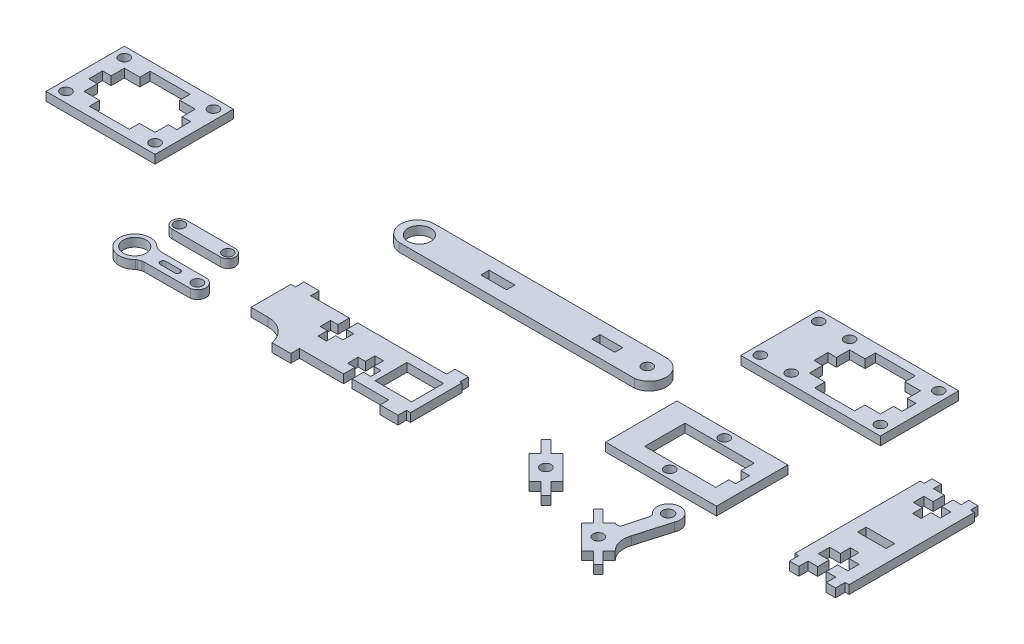
SolidWorks part; units mm, degrees
ref_plane "Front Plane" through (0, 0, 0) normal (0, 0, 1) x (1, 0, 0)
ref_plane "Top Plane" through (0, 0, 0) normal (0, 1, 0) x (1, 0, 0)
ref_plane "Right Plane" through (0, 0, 0) normal (1, 0, 0) x (0, 0, -1)
sketch "Sketch6" plane through (0, 0, -6.8736) normal (0, 1, 0) x (1, 0, 0)
  line L36 (172.3993, 17.524) -> (172.3993, 14.7799)
  line L37 (172.3993, 14.7799) -> (176.2794, 14.7799)
  line L38 (176.2794, 14.7799) -> (176.2794, 10.7799)
  line L39 (176.2794, 10.7799) -> (173.032, 10.7799)
  line L40 (173.032, 10.7799) -> (173.032, 7.063)
  line L41 (173.032, 7.063) -> (176.2794, 7.063)
  line L42 (176.2794, 7.063) -> (176.2794, 3.563)
  line L43 (176.2794, 3.563) -> (179.2794, 3.563)
  line L44 (179.2794, 3.563) -> (179.2794, 7.063)
  line L45 (179.2794, 7.063) -> (182.5439, 7.063)
  line L46 (182.5439, 7.063) -> (182.5439, 10.7799)
  line L47 (182.5439, 10.7799) -> (179.2794, 10.7799)
  line L48 (179.2794, 10.7799) -> (179.2794, 14.7799)
  line L49 (179.2794, 14.7799) -> (182.1277, 14.7799)
  line L50 (182.1277, 14.7799) -> (182.1277, 17.4216)
  line L54 (182.1277, -32.5784) -> (182.1277, -29.2201)
  line L55 (182.1277, -29.2201) -> (178.7635, -29.2201)
  line L56 (178.7635, -29.2201) -> (178.7635, -25.2201)
  line L57 (178.7635, -25.2201) -> (182.3404, -25.2201)
  line L58 (182.3404, -25.2201) -> (182.3404, -21.2526)
  line L59 (182.3404, -21.2526) -> (178.7635, -21.2526)
  line L60 (178.7635, -21.2526) -> (178.7635, -17.7526)
  line L61 (178.7635, -17.7526) -> (175.7635, -17.7526)
  line L62 (175.7635, -17.7526) -> (175.7635, -21.2526)
  line L63 (175.7635, -21.2526) -> (171.9828, -21.2526)
  line L64 (171.9828, -21.2526) -> (171.9828, -25.2201)
  line L65 (171.9828, -25.2201) -> (175.7635, -25.2201)
  line L66 (175.7635, -25.2201) -> (175.7635, -29.2201)
  line L67 (175.7635, -29.2201) -> (172.3993, -29.2201)
  line L68 (172.3993, -29.2201) -> (172.3993, -32.476)
  line L72 (172.2635, -8.7201) -> (182.2635, -8.7201)
  line L73 (182.2635, -8.7201) -> (182.2635, -11.7201)
  line L74 (182.2635, -11.7201) -> (172.2635, -11.7201)
  line L75 (172.2635, -11.7201) -> (172.2635, -8.7201)
  line L132 (186.7635, -29.2201) -> (185.3957, -29.2201)
  line L133 (185.3957, -29.2201) -> (185.3957, -32.5784)
  line L134 (167.7635, -29.2201) -> (169.1313, -29.2201)
  line L135 (169.1313, -29.2201) -> (169.1313, -32.476)
  line L136 (169.1313, 17.524) -> (169.1313, 14.7799)
  line L137 (169.1313, 14.7799) -> (167.7635, 14.7799)
  line L138 (185.3957, 17.4216) -> (185.3957, 14.7799)
  line L139 (185.3957, 14.7799) -> (186.7635, 14.7799)
  line L140 (167.7635, 14.7799) -> (167.7635, -29.2201)
  line L141 (169.1313, -32.476) -> (172.3993, -32.476)
  line L142 (182.1277, 17.4216) -> (185.3957, 17.4216)
  line L143 (186.7635, 14.7799) -> (186.7635, -29.2201)
  line L144 (185.3957, -32.5784) -> (182.1277, -32.5784)
  line L145 (169.1313, 17.524) -> (172.3993, 17.524)
  dimension "D6" = 1.3678
  dimension "D7" = 3.268
extrude "Boss-Extrude1" add sketch "Sketch6" along normal blind 3
sketch "Sketch12" plane through (0, 0, 0) normal (0, 1, 0) x (1, 0, 0)
  line L100 (4.3413, 14.5567) -> (85.6849, 14.5567)
  line L101 (3.678, 2.7449) -> (86.3482, 2.7449)
  line L103 (67.0131, 9.9945) -> (75.0131, 9.9945)
  line L104 (67.0131, 9.9945) -> (67.0131, 7.1945)
  line L105 (67.0131, 7.1945) -> (75.0131, 7.1945)
  line L106 (75.0131, 9.9945) -> (75.0131, 7.1945)
  line L107 (28.0131, 10.0945) -> (37.0131, 10.0945)
  line L108 (28.0131, 10.0945) -> (28.0131, 7.1945)
  line L109 (28.0131, 7.1945) -> (37.0131, 7.1945)
  line L110 (37.0131, 10.0945) -> (37.0131, 7.1945)
  arc A87 (4.3413, 14.5567) -> (3.678, 2.7449) centre (4.3413, 8.6322) ccw
  arc A88 (85.6849, 14.5567) -> (86.3482, 2.7449) centre (85.6849, 8.6322) cw
  circle A100 centre (5.0131, 8.5945) radius 4
  circle A101 centre (85.0131, 8.5945) radius 1.82
  dimension "D29" = 3.64
  dimension "D27" = 8
extrude "Boss-Extrude3" add sketch "Sketch12" along normal blind 3 separate body
sketch "Sketch14" plane through (0, 0, 0) normal (0, 1, 0) x (1, 0, 0)
  line L0 (20.7129, 62.7973) -> (80.7867, 62.7973)
  line L1 (80.7867, 62.7973) -> (80.7867, 17.6847)
  line L2 (80.7867, 17.6847) -> (20.7129, 17.6847)
  line L3 (20.7129, 17.6847) -> (20.7129, 62.7973)
  line L4 (28.2425, 59.822) -> (38.2425, 59.822)
  line L5 (28.2425, 59.822) -> (28.2425, 56.822)
  line L6 (28.2425, 56.822) -> (38.2425, 56.822)
  line L7 (38.2425, 59.822) -> (38.2425, 56.822)
  line L8 (63.2425, 59.822) -> (73.2425, 59.822)
  line L9 (63.2425, 59.822) -> (63.2425, 56.822)
  line L10 (63.2425, 56.822) -> (73.2425, 56.822)
  line L11 (73.2425, 59.822) -> (73.2425, 56.822)
  line L12 (74.7425, 59.822) -> (77.7425, 59.822)
  line L13 (74.7425, 59.822) -> (74.7425, 53.822)
  line L14 (74.7425, 53.822) -> (77.7425, 53.822)
  line L15 (77.7425, 59.822) -> (77.7425, 53.822)
  line L16 (74.7425, 46.822) -> (77.7425, 46.822)
  line L17 (74.7425, 46.822) -> (74.7425, 40.822)
  line L18 (74.7425, 40.822) -> (77.7425, 40.822)
  line L19 (77.7425, 46.822) -> (77.7425, 40.822)
  line L20 (29.7425, 35.822) -> (52.7425, 35.822)
  line L21 (29.7425, 35.822) -> (29.7425, 23.822)
  line L22 (29.7425, 23.822) -> (52.7425, 23.822)
  line L23 (52.7425, 35.822) -> (52.7425, 23.822)
  line L24 (23.7425, 46.822) -> (26.7425, 46.822)
  line L25 (23.7425, 46.822) -> (23.7425, 40.822)
  line L26 (23.7425, 40.822) -> (26.7425, 40.822)
  line L27 (26.7425, 46.822) -> (26.7425, 40.822)
  line L28 (23.7425, 59.822) -> (26.7425, 59.822)
  line L29 (23.7425, 59.822) -> (23.7425, 53.822)
  line L30 (23.7425, 53.822) -> (26.7425, 53.822)
  line L31 (26.7425, 59.822) -> (26.7425, 53.822)
  circle A0 centre (50.7425, 58.322) radius 1.82
  circle A1 centre (41.2425, 39.4969) radius 1.82
  circle A2 centre (41.2425, 20.3569) radius 1.82
  circle A3 centre (76.2425, 50.322) radius 1.82
  circle A4 centre (25.2425, 50.322) radius 1.82
  dimension "D1" = 19.14
  dimension "D2" = 3.64
  dimension "D3" = 3.64
  dimension "D4" = 3.64
  dimension "D5" = 3.64
extrude "Boss-Extrude4" [suppressed] add sketch "Sketch14" along normal blind 3 separate body
sketch "Sketch18" plane through (0, 0, 0) normal (0, 1, 0) x (1, 0, 0)
  line L0 (-52.2788, 74.8705) -> (7.7767, 74.8705)
  line L1 (7.7767, 74.8705) -> (7.7767, 31.3788)
  line L2 (7.7767, 31.3788) -> (0.9291, 20.5522)
  line L3 (0.9291, 20.5522) -> (-52.2788, 30.361)
  line L4 (-52.2788, 30.361) -> (-52.2788, 74.8705)
  line L5 (-44.7078, 71.6303) -> (-34.7078, 71.6303)
  line L6 (-44.7078, 71.6303) -> (-44.7078, 68.6303)
  line L7 (-44.7078, 68.6303) -> (-34.7078, 68.6303)
  line L8 (-34.7078, 71.6303) -> (-34.7078, 68.6303)
  line L9 (-49.2078, 71.6303) -> (-46.2078, 71.6303)
  line L10 (-49.2078, 71.6303) -> (-49.2078, 65.6303)
  line L11 (-49.2078, 65.6303) -> (-46.2078, 65.6303)
  line L12 (-46.2078, 71.6303) -> (-46.2078, 65.6303)
  line L13 (-49.2078, 58.6303) -> (-46.2078, 58.6303)
  line L14 (-49.2078, 58.6303) -> (-49.2078, 52.6303)
  line L15 (-49.2078, 52.6303) -> (-46.2078, 52.6303)
  line L16 (-46.2078, 58.6303) -> (-46.2078, 52.6303)
  line L17 (-43.2078, 47.6303) -> (-20.2078, 47.6303)
  line L18 (-43.2078, 47.6303) -> (-43.2078, 35.6303)
  line L19 (-43.2078, 35.6303) -> (-20.2078, 35.6303)
  line L20 (-20.2078, 47.6303) -> (-20.2078, 35.6303)
  line L21 (-9.7078, 71.6303) -> (0.2922, 71.6303)
  line L22 (-9.7078, 71.6303) -> (-9.7078, 68.6303)
  line L23 (-9.7078, 68.6303) -> (0.2922, 68.6303)
  line L24 (0.2922, 71.6303) -> (0.2922, 68.6303)
  line L25 (1.7922, 71.6303) -> (4.7922, 71.6303)
  line L26 (1.7922, 71.6303) -> (1.7922, 65.6303)
  line L27 (1.7922, 65.6303) -> (4.7922, 65.6303)
  line L28 (4.7922, 71.6303) -> (4.7922, 65.6303)
  line L29 (1.7922, 58.6303) -> (4.7922, 58.6303)
  line L30 (1.7922, 58.6303) -> (1.7922, 52.6303)
  line L31 (1.7922, 52.6303) -> (4.7922, 52.6303)
  line L32 (4.7922, 58.6303) -> (4.7922, 52.6303)
  circle A0 centre (3.3054, 62.1514) radius 1.82
  circle A1 centre (-0.9558, 24.7244) radius 1.2998
  circle A2 centre (-31.7081, 32.1289) radius 1.82
  circle A3 centre (-31.6898, 51.2689) radius 1.82
  circle A4 centre (-47.7078, 62.1303) radius 1.82
  circle A5 centre (-22.2078, 70.1303) radius 1.82
  dimension "D1" = 3.64
  dimension "D2" = 19.14
sketch "Sketch20" plane through (0, 0, 0) normal (0, 1, 0) x (1, 0, 0)
  line L0 (-3.3445, 5.1376) -> (-6.3445, 5.1376)
  line L1 (-6.3445, -0.1855) -> (-9.5309, -12.7114)
  line L2 (-21.2346, -12.8672) -> (-24.3389, -9.2481)
  line L3 (-24.3389, -9.2481) -> (-27.0786, -7.6072)
  line L4 (-27.0786, -7.6072) -> (-54.3445, -0.2275)
  line L5 (-54.3445, -0.2275) -> (-54.3445, 5.0581)
  line L6 (-54.3445, 5.0581) -> (-57.3445, 5.0581)
  line L7 (-57.3445, 5.0581) -> (-57.3445, 13.6523)
  line L8 (-57.3445, 13.6523) -> (-53.6006, 13.6523)
  line L9 (-53.6006, 13.6523) -> (-53.6006, 15.7725)
  line L10 (-53.6006, 15.7725) -> (-50.5945, 15.7725)
  line L11 (-50.5945, 15.7725) -> (-50.5945, 11.7725)
  line L12 (-50.5945, 11.7725) -> (-52.7659, 11.7725)
  line L13 (-52.7659, 11.7725) -> (-52.7659, 8.6302)
  line L14 (-52.7659, 8.6302) -> (-50.5945, 8.6302)
  line L15 (-50.5945, 8.6302) -> (-50.5945, 5.7725)
  line L16 (-50.5945, 5.7725) -> (-47.5945, 5.7725)
  line L17 (-47.5945, 5.7725) -> (-47.5945, 8.6302)
  line L18 (-47.5945, 8.6302) -> (-45.6767, 8.6302)
  line L19 (-45.6767, 8.6302) -> (-45.6767, 11.7725)
  line L20 (-45.6767, 11.7725) -> (-47.5945, 11.7725)
  line L21 (-47.5945, 11.7725) -> (-47.5945, 15.7725)
  line L22 (-47.5945, 15.7725) -> (-46.26, 15.7725)
  line L23 (-46.26, 15.7725) -> (-46.26, 14.5225)
  line L24 (-46.26, 14.5225) -> (-42.8445, 14.5225)
  line L25 (-42.8445, 14.5225) -> (-42.8445, 13.2725)
  line L26 (-42.8445, 13.2725) -> (-37.8445, 13.2725)
  line L27 (-37.8445, 13.2725) -> (-37.8445, 10.7725)
  line L28 (-37.8445, 10.7725) -> (-22.8445, 10.7725)
  line L29 (-22.8445, 10.7725) -> (-22.8445, 13.2725)
  line L30 (-22.8445, 13.2725) -> (-17.8445, 13.2725)
  line L31 (-17.8445, 13.2725) -> (-17.8445, 14.5225)
  line L32 (-17.8445, 14.5225) -> (-14.6403, 14.5225)
  line L33 (-14.6403, 14.5225) -> (-14.6403, 15.7725)
  line L34 (-14.6403, 15.7725) -> (-13.0945, 15.7725)
  line L35 (-13.0945, 15.7725) -> (-13.0945, 11.7725)
  line L36 (-13.0945, 11.7725) -> (-15.4488, 11.7725)
  line L37 (-15.4488, 11.7725) -> (-15.4488, 8.6851)
  line L38 (-15.4488, 8.6851) -> (-13.0945, 8.6851)
  line L39 (-13.0945, 8.6851) -> (-13.0945, 5.7725)
  line L40 (-13.0945, 5.7725) -> (-10.0945, 5.7725)
  line L41 (-10.0945, 5.7725) -> (-10.0945, 8.6674)
  line L42 (-10.0945, 8.6674) -> (-7.5507, 8.6674)
  line L43 (-7.5507, 8.6674) -> (-7.5507, 11.7725)
  line L44 (-7.5507, 11.7725) -> (-10.0945, 11.7725)
  line L45 (-10.0945, 11.7725) -> (-10.0945, 15.7725)
  line L46 (-10.0945, 15.7725) -> (-7.0098, 15.7725)
  line L47 (-7.0098, 15.7725) -> (-7.0098, 13.684)
  line L48 (-7.0098, 13.684) -> (-3.3445, 13.6514)
  line L49 (-3.3445, 13.6514) -> (-3.3445, 5.1376)
  line L50 (-6.3445, 5.1376) -> (-6.3445, -0.1855)
  arc A0 (-9.5309, -12.7114) -> (-21.2346, -12.8672) centre (-15.4037, -11.2174) cw
  circle A1 centre (-15.3445, -11.2275) radius 1.82
  dimension "D1" = 3.64
sketch "Sketch22" plane through (0, 0, 0) normal (0, 1, 0) x (1, 0, 0)
  line L0 (-22.8304, -83.5062) -> (5.98, -82.8529)
  line L1 (18.5125, -82.749) -> (92.2578, -82.749)
  line L2 (92.3104, -90.7487) -> (18.5715, -91.7184)
  line L3 (6.0387, -91.7793) -> (-22.7778, -91.5049)
  arc A0 (5.98, -82.8529) -> (10.0623, -81.6918) centre (5.7889, -74.4239) ccw
  arc A1 (10.0623, -81.6918) -> (10.658, -81.4927) centre (10.8295, -82.9967) cw
  arc A2 (10.658, -81.4927) -> (11.2714, -81.3569) centre (10.3161, -78.495) ccw
  arc A3 (11.2714, -81.3569) -> (11.8955, -81.2861) centre (11.7502, -82.7912) cw
  arc A4 (11.8955, -81.2861) -> (12.5237, -81.2808) centre (12.1844, -78.2942) ccw
  arc A5 (12.5237, -81.2808) -> (13.1489, -81.3413) centre (12.6941, -82.7806) cw
  arc A6 (13.1489, -81.3413) -> (13.7644, -81.4668) centre (14.0525, -78.4818) ccw
  arc A7 (13.7644, -81.4668) -> (14.3634, -81.656) centre (13.6195, -82.9685) cw
  arc A8 (14.3634, -81.656) -> (14.9394, -81.9067) centre (15.8391, -79.0526) ccw
  arc A9 (14.9394, -81.9067) -> (15.6165, -82.2065) centre (13.9387, -85.0813) cw
  arc A10 (15.6165, -82.2065) -> (16.3185, -82.4423) centre (16.5367, -80.6298) ccw
  arc A11 (16.3185, -82.4423) -> (17.0393, -82.6122) centre (15.9213, -85.7415) cw
  arc A12 (17.0393, -82.6122) -> (17.7727, -82.7147) centre (17.6534, -80.8935) ccw
  arc A13 (17.7727, -82.7147) -> (18.5125, -82.749) centre (17.9898, -86.0281) cw
  arc A14 (92.2578, -82.749) -> (92.3104, -90.7487) centre (92.2578, -86.7491) cw
  arc A15 (18.5715, -91.7184) -> (14.4371, -92.8659) centre (18.6822, -100.1392) ccw
  arc A16 (14.4371, -92.8659) -> (13.8407, -93.0629) centre (13.6751, -91.5605) cw
  arc A17 (13.8407, -93.0629) -> (13.2269, -93.1965) centre (14.1702, -96.0538) ccw
  arc A18 (13.2269, -93.1965) -> (12.6025, -93.2652) centre (12.753, -91.7611) cw
  arc A19 (12.6025, -93.2652) -> (11.9743, -93.2682) centre (12.3027, -96.2616) ccw
  arc A20 (11.9743, -93.2682) -> (11.3493, -93.2055) centre (11.8094, -91.7654) cw
  arc A21 (11.3493, -93.2055) -> (10.7342, -93.0779) centre (10.4346, -96.0685) ccw
  arc A22 (10.7342, -93.0779) -> (10.1359, -92.8866) centre (10.8846, -91.5762) cw
  arc A23 (10.1359, -92.8866) -> (9.5608, -92.6338) centre (8.6482, -95.4904) ccw
  arc A24 (9.5608, -92.6338) -> (8.8936, -92.3352) centre (10.5595, -89.5075) cw
  arc A25 (8.8936, -92.3352) -> (8.202, -92.0988) centre (7.9736, -93.8967) ccw
  arc A26 (8.202, -92.0988) -> (7.4916, -91.9264) centre (8.615, -88.8472) cw
  arc A27 (7.4916, -91.9264) -> (6.7685, -91.8196) centre (6.8709, -93.6279) ccw
  arc A28 (6.7685, -91.8196) -> (6.0387, -91.7793) centre (6.5832, -88.5467) cw
  arc A29 (-22.7778, -91.5049) -> (-22.8304, -83.5062) centre (-22.7397, -87.5052) cw
  circle A30 centre (-22.7398, -87.5051) radius 1.925
  circle A31 centre (12.2595, -87.275) radius 1.925
  circle A32 centre (92.2578, -86.749) radius 1.925
  dimension "D1" = 3.85
  dimension "D2" = 3.85
sketch "Sketch23" plane through (0, 0, 0) normal (0, 1, 0) x (1, 0, 0)
  line L0 (62.0938, -102.6123) -> (-12.185, -101.1529)
  line L1 (62.0145, -110.6115) -> (-11.7091, -110.5993)
  arc A0 (-18.7722, -99.8781) -> (-23.9525, -106.2408) centre (-18.181, -105.6496) ccw
  arc A1 (-23.9525, -106.2408) -> (-20.8301, -111.1061) centre (-17.5842, -105.5884) ccw
  arc A2 (-20.8301, -111.1061) -> (-15.5368, -111.3053) centre (-17.9986, -106.2928) ccw
  arc A3 (-15.5368, -111.3053) -> (-13.6142, -110.7239) centre (-12.8064, -116.8649) cw
  arc A4 (-13.6142, -110.7239) -> (-11.7091, -110.5993) centre (-11.7115, -125.1879) cw
  arc A5 (-18.7722, -99.8781) -> (-14.8108, -100.6548) centre (-18.0664, -106.7687) cw
  arc A6 (-14.8108, -100.6548) -> (-13.5188, -101.0143) centre (-13.353, -97.9172) ccw
  arc A7 (-13.5188, -101.0143) -> (-12.185, -101.1529) centre (-14.2348, -114.3916) cw
  arc A8 (62.0938, -102.6123) -> (62.0145, -110.6115) centre (62.0152, -106.6115) cw
  circle A9 centre (62.0152, -106.6115) radius 1.925
  circle A10 centre (-17.9809, -105.8257) radius 1.925
  dimension "D1" = 3.85
  dimension "D2" = 3.85
sketch "Sketch24" plane through (0, 0, 0) normal (0, 1, 0) x (1, 0, 0)
  line L0 (-90.2893, -24.7085) -> (-67.8284, -24.7085)
  line L1 (-90.2954, -32.7085) -> (-67.194, -32.744)
  line L2 (-75.2787, -28.7329) -> (-70.3703, -28.7329) construction
  line L3 (-75.2787, -27.7198) -> (-70.3703, -27.7198)
  line L4 (-75.2787, -29.7461) -> (-70.3703, -29.7461)
  arc A0 (-67.8284, -24.7085) -> (-62.5705, -23.1591) centre (-67.8284, -15.0125) ccw
  arc A1 (-62.5705, -23.1591) -> (-54.9836, -31.523) centre (-60.3229, -28.7434) cw
  arc A2 (-54.9836, -31.523) -> (-63.9473, -33.5823) centre (-60.343, -28.7329) cw
  arc A3 (-67.194, -32.744) -> (-63.9473, -33.5823) centre (-67.2043, -39.4905) cw
  arc A4 (-75.2787, -27.7198) -> (-75.2787, -29.7461) centre (-75.2787, -28.7329) ccw
  arc A5 (-70.3703, -29.7461) -> (-70.3703, -27.7198) centre (-70.3703, -28.7329) ccw
  circle A6 centre (-90.2893, -28.7085) radius 1.925
  circle A7 centre (-60.2893, -28.7085) radius 4
  arc A8 (-90.2954, -32.7085) -> (-90.2893, -24.7085) centre (-90.2893, -28.7085) cw
  point P13 (-72.8245, -28.7329)
  dimension "D1" = 3.85
  dimension "D2" = 8
sketch "Sketch26" plane through (0, 0, 0) normal (0, 1, 0) x (1, 0, 0)
  line L0 (-87.7528, 74.718) -> (-87.4104, 72.6313)
  line L1 (-87.7528, 74.718) -> (-88.0164, 76.816)
  arc A0 (-88.0164, 76.816) -> (-95.8236, 75.1147) centre (-92.0067, 76.3629) ccw
  arc A1 (-95.8236, 75.1147) -> (-95.7872, 31.4073) centre (-162.8228, 53.2052) cw
  arc A2 (-95.7872, 31.4073) -> (-88.3346, 28.5226) centre (-91.9816, 30.1698) ccw
  arc A3 (-88.3346, 28.5226) -> (-75.123, 36.3095) centre (-76.205, 23.044) cw
  arc A4 (-75.123, 36.3095) -> (-71.9331, 43.1193) centre (-74.7969, 40.3087) ccw
  arc A5 (-71.9331, 43.1193) -> (-87.4104, 72.6313) centre (-30.7636, 83.5248) cw
  circle A6 centre (-74.764, 40.2933) radius 1.82
  circle A7 centre (-91.9939, 30.1381) radius 1.82
  circle A8 centre (-91.9939, 76.3923) radius 1.82
  dimension "D1" = 3.64
  dimension "D2" = 3.64
  dimension "D3" = 3.64
sketch "Sketch27" plane through (0, 0, 0) normal (0, 1, 0) x (1, 0, 0)
  line L0 (-91.9831, 11.0737) -> (-77.9831, 11.0737)
  line L1 (-104.1231, 14.1616) -> (-65.8431, 14.1616)
  line L2 (-104.1231, 14.1616) -> (-104.1231, -13.3284)
  line L3 (-104.1231, -13.3284) -> (-65.8431, -13.3284)
  line L4 (-65.8431, 14.1616) -> (-65.8431, -13.3284)
  line L5 (-77.9831, 11.0737) -> (-77.9831, 7.4737)
  line L6 (-77.9831, 7.4737) -> (-72.5331, 7.4737)
  line L7 (-72.5331, 7.4737) -> (-72.5331, 2.8437)
  line L8 (-69.5331, 2.8437) -> (-69.5331, -2.0063)
  line L9 (-69.5331, -2.0063) -> (-72.5331, -2.0063)
  line L10 (-72.5331, -2.0063) -> (-72.5331, -6.6363)
  line L11 (-72.5331, -6.6363) -> (-77.9831, -6.6363)
  line L12 (-77.9831, -6.6363) -> (-77.9831, -10.2363)
  line L13 (-77.9831, -10.2363) -> (-91.9831, -10.2363)
  line L14 (-91.9831, -10.2363) -> (-91.9831, -6.6384)
  line L15 (-91.9831, -6.6384) -> (-97.4331, -6.6384)
  line L16 (-97.4331, -6.6384) -> (-97.4331, -2.0084)
  line L17 (-97.4331, -2.0084) -> (-100.4331, -2.0084)
  line L18 (-100.4331, -2.0084) -> (-100.4331, 2.8416)
  line L19 (-100.4331, 2.8416) -> (-97.4331, 2.8416)
  line L20 (-97.4331, 2.8416) -> (-97.4331, 7.4716)
  line L21 (-97.4331, 7.4716) -> (-91.9831, 7.4716)
  line L22 (-91.9831, 7.4716) -> (-91.9831, 11.0737)
  line L23 (-72.5331, 2.8437) -> (-69.5331, 2.8437)
  circle A0 centre (-100.6231, 10.6616) radius 1.82
  circle A1 centre (-100.6231, -9.8284) radius 1.82
  circle A2 centre (-69.3431, -9.8263) radius 1.82
  circle A3 centre (-69.3431, 10.6616) radius 1.82
  dimension "D1" = 3.64
  dimension "D2" = 14
  dimension "D3" = 3.6
  dimension "D4" = 3.6
  dimension "D5" = 4.85
  dimension "D6" = 4.63
  dimension "D7" = 3.19
  dimension "D8" = 3.19
  dimension "D9" = 3.19
  dimension "D10" = 5.45
  dimension "D11" = 3
  dimension "D12" = 3.19
  dimension "D13" = 3.19
  dimension "D14" = 3.19
  dimension "D15" = 3.5
  dimension "D16" = 3.5
  dimension "D17" = 3.5
sketch "Sketch28" plane through (0, 0, 0) normal (0, 1, 0) x (1, 0, 0)
  line L0 (108.8597, -2.0432) -> (133.1497, -2.0432)
  line L1 (100.7124, 3.3321) -> (139.6281, 3.3321)
  line L2 (100.7124, 3.3321) -> (100.7124, -21.7433)
  line L3 (100.7124, -21.7433) -> (139.6281, -21.7433)
  line L4 (139.6281, 3.3321) -> (139.6281, -21.7433)
  line L5 (133.1497, -2.0432) -> (133.1497, -6.6732)
  line L6 (133.1497, -6.6732) -> (136.1497, -6.6732)
  line L7 (136.1497, -6.6732) -> (136.1497, -11.5232)
  line L8 (136.1497, -11.5232) -> (133.7949, -11.5232)
  line L9 (133.7949, -11.5232) -> (133.7949, -16.1532)
  line L10 (133.7949, -16.1532) -> (108.8597, -16.1532)
  line L11 (108.8597, -16.1532) -> (108.8597, -2.0432)
  circle A0 centre (120.2396, 0.384) radius 1.82
  circle A1 centre (120.2396, -18.756) radius 1.82
  dimension "D1" = 3.64
  dimension "D2" = 3.64
  dimension "D3" = 3
  dimension "D4" = 24.29
  dimension "D5" = 4.85
  dimension "D6" = 4.63
  dimension "D7" = 19.14
sketch "Sketch29" plane through (0, 0, 0) normal (0, 1, 0) x (1, 0, 0)
  line L0 (120.9256, 52.7526) -> (134.9256, 52.7526)
  line L1 (98.079, 55.8405) -> (147.0656, 55.8405)
  line L2 (98.079, 55.8405) -> (98.079, 28.3505)
  line L3 (98.079, 28.3505) -> (147.0656, 28.3505)
  line L4 (147.0656, 55.8405) -> (147.0656, 28.3505)
  line L5 (134.9256, 52.7526) -> (134.9256, 49.1526)
  line L6 (134.9256, 49.1526) -> (140.3756, 49.1526)
  line L7 (140.3756, 49.1526) -> (140.3756, 44.5226)
  line L8 (143.3756, 44.5226) -> (143.3756, 39.6726)
  line L9 (143.3756, 39.6726) -> (140.3756, 39.6726)
  line L10 (140.3756, 39.6726) -> (140.3756, 35.0426)
  line L11 (140.3756, 35.0426) -> (134.9256, 35.0426)
  line L12 (134.9256, 35.0426) -> (134.9256, 31.4426)
  line L13 (134.9256, 31.4426) -> (120.9256, 31.4426)
  line L14 (120.9256, 31.4426) -> (120.9256, 35.0405)
  line L15 (120.9256, 35.0405) -> (115.4756, 35.0405)
  line L16 (115.4756, 35.0405) -> (115.4756, 39.6705)
  line L17 (115.4756, 39.6705) -> (112.4756, 39.6705)
  line L18 (112.4756, 39.6705) -> (112.4756, 44.5205)
  line L19 (112.4756, 44.5205) -> (115.4756, 44.5205)
  line L20 (115.4756, 44.5205) -> (115.4756, 49.1505)
  line L21 (115.4756, 49.1505) -> (120.9256, 49.1505)
  line L22 (120.9256, 49.1505) -> (120.9256, 52.7526)
  line L23 (140.3756, 44.5226) -> (143.3756, 44.5226)
  circle A0 centre (112.2856, 52.3405) radius 1.82
  circle A1 centre (112.2856, 31.8505) radius 1.82
  circle A2 centre (143.5656, 31.8526) radius 1.82
  circle A3 centre (143.5656, 52.3405) radius 1.82
  circle A4 centre (101.4197, 52.3405) radius 1.82
  circle A5 centre (101.4197, 31.8505) radius 1.82
  dimension "D1" = 3.64
  dimension "D2" = 14
  dimension "D3" = 3.6
  dimension "D4" = 3.6
  dimension "D5" = 4.85
  dimension "D6" = 4.63
  dimension "D7" = 3.19
  dimension "D8" = 3.19
  dimension "D9" = 3.19
  dimension "D10" = 5.45
  dimension "D11" = 3
  dimension "D12" = 3.19
  dimension "D13" = 3.1879
  dimension "D14" = 3.19
  dimension "D15" = 3.5
  dimension "D16" = 3.5
  dimension "D17" = 20.49
sketch "Sketch30" plane through (0, 0, 0) normal (0, 1, 0) x (1, 0, 0)
  line L0 (17.989, -28.9872) -> (4.4448, -28.9872)
  line L1 (11.9231, -50.0571) -> (18.5165, -50.0571)
  line L2 (18.5165, -50.0571) -> (18.5165, -46.9872)
  line L3 (18.5165, -46.9872) -> (33.989, -46.9872)
  line L4 (33.989, -46.9872) -> (33.989, -42.9872)
  line L5 (33.989, -42.9872) -> (31.4392, -42.9872)
  line L6 (31.4392, -42.9872) -> (31.4392, -39.3422)
  line L7 (31.4392, -39.3422) -> (33.989, -39.3422)
  line L8 (33.989, -39.3422) -> (33.989, -35.9872)
  line L9 (33.989, -35.9872) -> (36.989, -35.9872)
  line L10 (36.989, -35.9872) -> (36.989, -39.3774)
  line L11 (36.989, -39.3774) -> (39.5388, -39.3774)
  line L12 (39.5388, -39.3774) -> (39.5388, -42.9872)
  line L13 (39.5388, -42.9872) -> (36.989, -42.9872)
  line L14 (36.989, -42.9872) -> (36.989, -46.9872)
  line L15 (36.989, -46.9872) -> (49.8067, -46.9872)
  line L16 (49.8067, -46.9872) -> (49.8067, -49.9872)
  line L17 (52.1127, -25.9872) -> (52.1127, -28.9872)
  line L18 (52.1127, -28.9872) -> (20.989, -28.9872)
  line L19 (20.989, -28.9872) -> (20.989, -32.9872)
  line L20 (20.989, -32.9872) -> (23.539, -32.9872)
  line L21 (23.539, -32.9872) -> (23.539, -36.7505)
  line L22 (23.539, -36.7505) -> (20.989, -36.7505)
  line L23 (20.989, -36.7505) -> (20.989, -39.9872)
  line L24 (20.989, -39.9872) -> (17.989, -39.9872)
  line L25 (17.989, -39.9872) -> (17.989, -36.6921)
  line L26 (17.989, -36.6921) -> (15.439, -36.6921)
  line L27 (15.439, -36.6921) -> (15.439, -32.9872)
  line L28 (15.439, -32.9872) -> (17.989, -32.9872)
  line L29 (17.989, -32.9872) -> (17.989, -28.9872)
  line L30 (4.4448, -28.9872) -> (4.4448, -25.9872)
  line L31 (41.6011, -32.3441) -> (54.4301, -32.3441)
  line L32 (41.6011, -32.3441) -> (41.6011, -43.5339)
  line L33 (41.6011, -43.5339) -> (54.4301, -43.5339)
  line L34 (54.4301, -32.3441) -> (54.4301, -43.5339)
  line L35 (-2.511, -42.9872) -> (3.489, -42.9872)
  line L36 (-0.8977, -25.9872) -> (-0.8977, -28.9872)
  line L37 (-0.8977, -28.9872) -> (-2.511, -28.9872)
  line L38 (56.0898, -49.9872) -> (56.0898, -46.9872)
  line L39 (56.0898, -46.9872) -> (57.489, -46.9872)
  line L40 (56.7962, -25.9872) -> (56.7962, -28.9872)
  line L41 (56.7962, -28.9872) -> (57.489, -28.9872)
  line L42 (57.489, -28.9872) -> (57.489, -46.9872)
  line L43 (56.0898, -49.9872) -> (49.8067, -49.9872)
  line L44 (56.7962, -25.9872) -> (52.1127, -25.9872)
  line L45 (-0.8977, -25.9872) -> (4.4448, -25.9872)
  line L46 (-2.511, -42.9872) -> (-2.511, -28.9872)
  arc A0 (3.489, -42.9872) -> (11.9231, -50.0571) centre (3.489, -51.5529) cw
  dimension "D1" = 3.645
  dimension "D2" = 2.5498
  dimension "D3" = 2.55
  dimension "D4" = 2.55
  dimension "D5" = 2.55
  dimension "D6" = 2.55
sketch "Sketch31" plane through (0, 0, 0) normal (0, 1, 0) x (1, 0, 0)
  line L0 (-40.1799, -27.8411) -> (-23.1799, -27.8411)
  line L1 (-23.1799, -33.0411) -> (-40.1799, -33.0411)
  arc A0 (-23.1799, -27.8411) -> (-23.1799, -33.0411) centre (-23.1799, -30.4411) cw
  arc A1 (-40.1799, -33.0411) -> (-40.1799, -27.8411) centre (-40.1799, -30.4411) cw
  circle A2 centre (-40.1799, -30.4411) radius 1.82
  circle A3 centre (-23.1799, -30.4411) radius 1.82
  dimension "D1" = 3.64
  dimension "D2" = 3.64
  dimension "D3" = 2.6
  dimension "D4" = 2.6
  dimension "D5" = 2.6
sketch "Sketch32" plane through (0, 0, 0) normal (0, 1, 0) x (1, 0, 0)
  line L0 (-19.3691, -41.9276) -> (-34.5684, -41.9276)
  line L1 (-18.8998, -47.8907) -> (-35.1542, -47.962)
  line L2 (-35.1542, -47.962) -> (-35.7319, -48.0649)
  line L3 (-31.4441, -44.9276) -> (-26.3849, -44.9276) construction
  line L4 (-31.4441, -43.9544) -> (-26.3849, -43.9544)
  line L5 (-31.4441, -45.9008) -> (-26.3849, -45.9008)
  arc A0 (-34.5684, -41.9276) -> (-38.333, -40.3416) centre (-34.5684, -36.6667) cw
  arc A1 (-38.333, -40.3416) -> (-42.1025, -50.3785) centre (-41.3099, -44.9499) ccw
  arc A2 (-42.1025, -50.3785) -> (-37.3382, -48.7649) centre (-41.3026, -44.9) ccw
  arc A3 (-37.3382, -48.7649) -> (-36.8315, -48.4691) centre (-36.5499, -49.5334) cw
  arc A4 (-36.8315, -48.4691) -> (-35.7319, -48.0649) centre (-38.4338, -42.4122) ccw
  arc A5 (-19.3691, -41.9276) -> (-18.8998, -47.8907) centre (-19.3691, -44.9276) cw
  arc A6 (-31.4441, -43.9544) -> (-31.4441, -45.9008) centre (-31.4441, -44.9276) ccw
  arc A7 (-26.3849, -45.9008) -> (-26.3849, -43.9544) centre (-26.3849, -44.9276) ccw
  circle A8 centre (-41.3691, -44.9276) radius 4
  circle A9 centre (-19.3691, -44.9276) radius 1.82
  point P17 (-28.9145, -44.9276)
  dimension "D1" = 3.64
sketch "Sketch33" plane through (0, 0, 0) normal (0, 1, 0) x (1, 0, 0)
  line L0 (-4.2145, -66.2122) -> (75.574, -66.2122) construction
  line L1 (-4.2145, -62.1261) -> (75.574, -62.1261)
  line L2 (-4.2145, -70.2983) -> (75.574, -70.2983)
  arc A0 (-4.2145, -62.1261) -> (-4.2145, -70.2983) centre (-4.2145, -66.2122) ccw
  arc A1 (75.574, -70.2983) -> (75.574, -62.1261) centre (75.574, -66.2122) ccw
  circle A2 centre (-4.3278, -66.2456) radius 1.87
  circle A3 centre (75.6722, -66.2456) radius 1.87
  point P2 (35.6798, -66.2122)
  dimension "D1" = 3.74
  dimension "D2" = 3.74
sketch "Sketch34" plane through (0, 0, 0) normal (0, 1, 0) x (1, 0, 0)
  line L0 (85.46, -5.1233) -> (5.46, -5.1233)
  line L1 (5.3693, -17.1401) -> (85.46, -17.1233)
  line L2 (85.46, -17.1401) -> (85.46, -17.1233)
  line L3 (15.46, -9.6233) -> (22.96, -9.6233)
  line L4 (15.46, -9.6233) -> (15.46, -12.6233)
  line L5 (15.46, -12.6233) -> (22.96, -12.6233)
  line L6 (22.96, -9.6233) -> (22.96, -12.6233)
  line L7 (70.46, -9.6233) -> (75.46, -9.6233)
  line L8 (70.46, -9.6233) -> (70.46, -12.6233)
  line L9 (70.46, -12.6233) -> (75.46, -12.6233)
  line L10 (75.46, -9.6233) -> (75.46, -12.6233)
  arc A0 (5.46, -5.1233) -> (5.3693, -17.1401) centre (5.4147, -11.1317) ccw
  arc A1 (85.46, -5.1233) -> (85.46, -17.1401) centre (85.46, -11.1317) cw
  circle A2 centre (85.46, -11.1233) radius 1.82
  circle A3 centre (37.46, -11.1233) radius 1.82
  circle A4 centre (5.46, -11.1233) radius 1.82
  dimension "D1" = 3.64
  dimension "D2" = 3.64
  dimension "D3" = 3.64
sketch "Sketch35" plane through (0, 0, 0) normal (0, 1, 0) x (1, 0, 0)
  circle A0 centre (114.4508, 13.6733) radius 1.925
  circle A1 centre (114.4508, 13.6733) radius 5
  dimension "D1" = 3.85
sketch "Sketch36" plane through (0, 0, 0) normal (0, 1, 0) x (1, 0, 0)
  line L0 (96.6735, -32.7093) -> (105.1588, -41.1946)
  line L1 (105.1588, -41.1946) -> (103.0375, -43.3159)
  line L2 (103.0375, -43.3159) -> (107.2801, -47.5586)
  line L3 (107.2801, -47.5586) -> (105.583, -49.2556)
  line L4 (105.583, -49.2556) -> (101.3404, -45.013)
  line L5 (101.3404, -45.013) -> (99.2191, -47.1343)
  line L6 (99.2191, -47.1343) -> (90.7338, -38.6491)
  line L7 (90.7338, -38.6491) -> (92.8551, -36.5277)
  line L8 (92.8551, -36.5277) -> (88.6125, -32.2851)
  line L9 (88.6125, -32.2851) -> (90.3095, -30.588)
  line L10 (90.3095, -30.588) -> (94.5522, -34.8307)
  line L11 (94.5522, -34.8307) -> (96.6735, -32.7093)
  circle A0 centre (97.9463, -39.9218) radius 1.82
  dimension "D1" = 3.64
sketch "Sketch37" plane through (0, 0, 0) normal (0, 1, 0) x (1, 0, 0)
  line L0 (135.4169, -53.0651) -> (133.2956, -55.1864)
  line L1 (133.2956, -55.1864) -> (137.5382, -59.4291)
  line L2 (137.5382, -59.4291) -> (135.8412, -61.1261)
  line L3 (135.8412, -61.1261) -> (131.5985, -56.8835)
  line L4 (131.5985, -56.8835) -> (129.4772, -59.0048)
  line L5 (129.4772, -59.0048) -> (120.9919, -50.5195)
  line L6 (120.9919, -50.5195) -> (123.1132, -48.3982)
  line L7 (123.1132, -48.3982) -> (118.8706, -44.1556)
  line L8 (118.8706, -44.1556) -> (120.5677, -42.4585)
  line L9 (120.5677, -42.4585) -> (124.8103, -46.7012)
  line L10 (124.8103, -46.7012) -> (126.9316, -44.5798)
  line L11 (129.1898, -43.6445) -> (131.0313, -36.7977)
  line L12 (133.7199, -45.6405) -> (137.1051, -33.9217)
  line L13 (131.0313, -36.7977) -> (131.0313, -35.5609)
  arc A0 (126.9316, -44.5798) -> (129.1898, -43.6445) centre (127.867, -43.6445) ccw
  arc A1 (135.4169, -53.0651) -> (133.7199, -45.6405) centre (140.4805, -48.0015) cw
  circle A2 centre (133.3808, -32.4738) radius 1.925
  arc A3 (137.1051, -33.9217) -> (131.0313, -35.5609) centre (133.4056, -32.2861) ccw
  circle A4 centre (128.2044, -51.7923) radius 1.8201
  dimension "D1" = 3.6402
  dimension "D2" = 3.85
sketch "Sketch38" plane through (0, 0, 0) normal (0, 1, 0) x (1, 0, 0)
  line L0 (214.8986, 72.4925) -> (211.8986, 72.4925)
  line L1 (211.8986, 72.4925) -> (211.8986, 59.0158)
  line L2 (211.8986, 59.0158) -> (207.8986, 59.0158)
  line L3 (207.8986, 59.0158) -> (207.8986, 62.9131)
  line L4 (207.8986, 62.9131) -> (203.2662, 63.0537)
  line L5 (203.2662, 63.0537) -> (203.2662, 59.0158)
  line L6 (203.2662, 59.0158) -> (201.8986, 59.0158)
  line L7 (201.8986, 59.0158) -> (201.8986, 56.0158)
  line L8 (201.8986, 56.0158) -> (203.2651, 56.0158)
  line L9 (203.2651, 56.0158) -> (203.2651, 52.2449)
  line L10 (203.2651, 52.2449) -> (207.8986, 52.2911)
  line L11 (207.8986, 52.2911) -> (207.8986, 56.0158)
  line L12 (207.8986, 56.0158) -> (211.8986, 56.0158)
  line L13 (211.8986, 56.0158) -> (211.8986, 42.6429)
  line L14 (211.8986, 42.6429) -> (214.8986, 42.6429)
  line L15 (164.8986, 42.6429) -> (167.6736, 42.6429)
  line L16 (167.8986, 56.962) -> (171.8986, 56.962)
  line L17 (171.8986, 56.962) -> (171.8986, 53.4656)
  line L18 (171.8986, 53.4656) -> (176.3141, 53.6437)
  line L19 (176.3141, 53.6437) -> (176.3141, 56.962)
  line L20 (176.3141, 56.962) -> (177.8986, 56.962)
  line L21 (177.8986, 56.962) -> (177.8986, 59.6133)
  line L22 (177.8986, 59.6133) -> (176.1034, 59.6133)
  line L23 (176.1034, 59.6133) -> (176.1034, 63.1125)
  line L24 (176.1034, 63.1125) -> (171.8986, 63.1125)
  line L25 (171.8986, 63.1125) -> (171.8986, 59.6133)
  line L26 (171.8986, 59.6133) -> (167.8986, 59.6133)
  line L27 (167.8986, 59.6133) -> (167.8986, 72.4925)
  line L28 (167.8986, 72.4925) -> (164.8986, 72.4925)
  line L29 (167.6736, 42.6429) -> (167.8986, 56.962)
  line L30 (214.8986, 37.2429) -> (211.4066, 37.2429)
  line L31 (211.4066, 37.2429) -> (211.4066, 34.6032)
  line L32 (164.8986, 37.2429) -> (168.3401, 37.2429)
  line L33 (168.3401, 37.2429) -> (168.3401, 34.6032)
  line L34 (214.8986, 37.2429) -> (214.8986, 42.6429)
  line L35 (211.4066, 34.6032) -> (168.3401, 34.6032)
  line L36 (164.8986, 37.2429) -> (164.8986, 42.6429)
  line L37 (210.8826, 80.5322) -> (210.8826, 77.8925)
  line L38 (210.8826, 77.8925) -> (214.8986, 77.8925)
  line L39 (164.8986, 77.8925) -> (169.2475, 77.8925)
  line L40 (169.2475, 77.8925) -> (169.2475, 80.5322)
  line L41 (169.2475, 80.5322) -> (210.8826, 80.5322)
  line L42 (164.8986, 77.8925) -> (164.8986, 72.4925)
  line L43 (214.8986, 72.4925) -> (214.8986, 77.8925)
  circle A0 centre (189.8986, 58.0322) radius 3.75
  circle A1 centre (182.8986, 58.0322) radius 1.5333
  circle A2 centre (189.889, 69.1146) radius 1.4239
  circle A3 centre (196.8493, 58.0203) radius 1.6482
  circle A4 centre (192.8986, 76.7822) radius 1.82
  circle A5 centre (189.8986, 47.0381) radius 1.3524
  circle A6 centre (192.885, 39.1928) radius 1.82
  dimension "D6" = 3.64
  dimension "D7" = 3.64
  dimension "D1" = 5.4
  dimension "D2" = 5.4
  dimension "D3" = 5.4
  dimension "D4" = 5.4
  dimension "D5" = 2.6397
extrude "Boss-Extrude5" [suppressed] add sketch "Sketch18" along normal blind 3 separate body
extrude "Boss-Extrude6" [suppressed] add sketch "Sketch38" along normal blind 3 separate body
extrude "Boss-Extrude7" add sketch "Sketch37" along normal blind 3 separate body
extrude "Boss-Extrude8" add sketch "Sketch36" along normal blind 3 separate body
extrude "Boss-Extrude9" [suppressed] add sketch "Sketch35" along normal blind 3 separate body
extrude "Boss-Extrude10" [suppressed] add sketch "Sketch34" along normal blind 3 separate body
extrude "Boss-Extrude11" [suppressed] add sketch "Sketch33" along normal blind 3 separate body
extrude "Boss-Extrude12" add sketch "Sketch32" along normal blind 3 separate body
extrude "Boss-Extrude13" add sketch "Sketch31" along normal blind 3 separate body
extrude "Boss-Extrude14" add sketch "Sketch30" along normal blind 3 separate body
extrude "Boss-Extrude15" add sketch "Sketch29" along normal blind 3 separate body
extrude "Boss-Extrude16" add sketch "Sketch28" along normal blind 3 separate body
extrude "Boss-Extrude17" add sketch "Sketch27" along normal blind 3 separate body
extrude "Boss-Extrude18" [suppressed] add sketch "Sketch26" along normal blind 3 separate body
extrude "Boss-Extrude19" [suppressed] add sketch "Sketch24" along normal blind 3 separate body
extrude "Boss-Extrude20" [suppressed] add sketch "Sketch23" along normal blind 3 separate body
extrude "Boss-Extrude21" [suppressed] add sketch "Sketch22" along normal blind 3 separate body
extrude "Boss-Extrude22" [suppressed] add sketch "Sketch20" along normal blind 3 separate body
sketch "Sketch41" plane through (0, 0, 0) normal (0, 1, 0) x (1, 0, 0)
  line L0 (218.7805, -81.1114) -> (254.3702, -116.7011)
  line L1 (151.2617, -33.8089) -> (296.4281, -33.8089)
  line L2 (151.2617, -33.8089) -> (151.2617, -128.5401)
  line L3 (151.2617, -128.5401) -> (296.4281, -128.5401)
  line L4 (296.4281, -33.8089) -> (296.4281, -128.5401)
  line L5 (254.3702, -116.7011) -> (289.8339, -81.2374)
  line L6 (289.8339, -81.2374) -> (254.2442, -45.6477)
  line L7 (254.2442, -45.6477) -> (218.7805, -81.1114)
  circle A0 centre (232.313, -59.3089) radius 1.82
  circle A1 centre (194.813, -49.5089) radius 1.82
  circle A2 centre (166.913, -49.5089) radius 1.82
  circle A3 centre (161.813, -101.6089) radius 1.82
  circle A4 centre (210.013, -100.3089) radius 1.82
  circle A5 centre (232.313, -103.3089) radius 1.82
  circle A6 centre (276.313, -103.3089) radius 1.82
  circle A7 centre (276.313, -59.3089) radius 1.82
  dimension "D1" = 3.64
extrude "Boss-Extrude23" [suppressed] add sketch "Sketch41" along normal blind 3 separate body
sketch "Sketch42" plane through (0, 0, 0) normal (0, 1, 0) x (1, 0, 0)
  line L0 (-109.4446, -51.7385) -> (-59.3919, -51.7385)
  line L1 (-109.4446, -51.7385) -> (-109.4446, -101.6556)
  line L2 (-109.4446, -101.6556) -> (-59.3919, -101.6556)
  line L3 (-59.3919, -51.7385) -> (-59.3919, -101.6556)
  line L4 (-95.8417, -82.5662) -> (-72.6942, -82.5662)
  line L5 (-95.8417, -82.5662) -> (-95.8417, -70.7669)
  line L6 (-95.8417, -70.7669) -> (-72.6942, -70.7669)
  line L7 (-72.6942, -82.5662) -> (-72.6942, -70.7669)
  circle A0 centre (-106.3103, -54.7462) radius 1.82
  circle A1 centre (-84.3064, -66.8836) radius 1.82
  circle A2 centre (-62.3037, -54.735) radius 1.82
  circle A3 centre (-84.3093, -86.0236) radius 1.82
  circle A4 centre (-62.3053, -98.732) radius 1.82
  circle A5 centre (-106.3086, -98.7412) radius 1.82
  dimension "D1" = 19.14
  dimension "D2" = 3.64
extrude "Boss-Extrude24" [suppressed] add sketch "Sketch42" along normal blind 3 separate body
